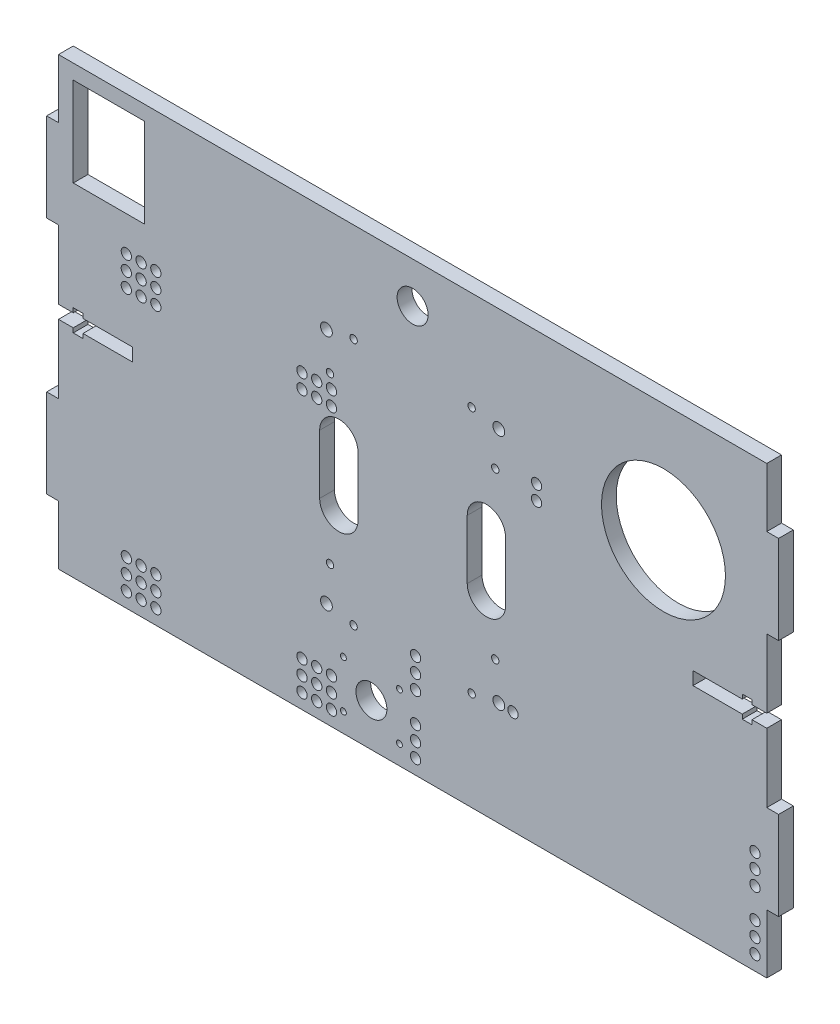
SolidWorks part; units mm, degrees
ref_plane "Front Plane" through (0, 0, 0) normal (0, 0, 1) x (1, 0, 0)
ref_plane "Top Plane" through (0, 0, 0) normal (0, 1, 0) x (1, 0, 0)
ref_plane "Right Plane" through (0, 0, 0) normal (1, 0, 0) x (0, 0, -1)
sketch "Sketch1" plane through (0, 0, 0) normal (0, 0, 1) x (1, 0, 0)
  line L1 (-120, 75.5) -> (120, 75.5)
  line L2 (-120, 75.5) -> (-120, -75.5)
  line L3 (-120, -75.5) -> (120, -75.5)
  line L4 (120, 75.5) -> (120, -75.5)
  dimension "D1" = 240
  dimension "D2" = 120
  dimension "D3" = 151
  dimension "D4" = 75.5
extrude "Boss-Extrude1" add sketch "Sketch1" along normal blind 5
sketch "Sketch2" plane through (0, 0, 0) normal (0, 0, -1) x (-1, 0, 0)
  line L0 (0, 0) -> (54.8158, 0) construction
  circle A0 centre (-20, 42) radius 1.25
  circle A1 centre (28, 28) radius 1.25
  circle A2 centre (20, 42) radius 1.25
  circle A3 centre (-28, 28) radius 1.25
  circle A4 centre (-28, -28) radius 1.25
  circle A5 centre (20, -42) radius 1.25
  circle A6 centre (28, -28) radius 1.25
  circle A7 centre (-20, -42) radius 1.25
extrude "Cut-Extrude1" cut sketch "Sketch2" against normal blind 5
sketch "Sketch5" plane through (0, 0, 0) normal (0, 0, -1) x (-1, 0, 0)
  line L0 (25, -10.5) -> (25, 9.5) construction
  line L1 (18.5, -10.5) -> (18.5, 9.5)
  line L2 (31.5, -10.5) -> (31.5, 9.5)
  line L3 (0, 0) -> (0, -34.3019) construction
  line L4 (-25, -10.5) -> (-25, 9.5) construction
  line L5 (-18.5, -10.5) -> (-18.5, 9.5)
  line L6 (-31.5, -10.5) -> (-31.5, 9.5)
  arc A0 (18.5, -10.5) -> (31.5, -10.5) centre (25, -10.5) ccw
  arc A1 (31.5, 9.5) -> (18.5, 9.5) centre (25, 9.5) ccw
  arc A2 (-18.5, -10.5) -> (-31.5, -10.5) centre (-25, -10.5) cw
  circle A3 centre (28, 28) radius 1.25 construction
  arc A4 (-31.5, 9.5) -> (-18.5, 9.5) centre (-25, 9.5) cw
  point P2 (25, -0.5)
  point P14 (-25, -0.5)
  dimension "D1" = 3
  dimension "D2" = 18.5
  dimension "D3" = 13
  dimension "D4" = 20
extrude "Cut-Extrude2" cut sketch "Sketch5" against normal blind 10
sketch "Sketch7" plane through (0, 0, 0) normal (0, 0, -1) x (-1, 0, 0)
  line L0 (0, 0) -> (0, -54.3684) construction
  line L1 (49.7043, 0) -> (71.9806, 0) construction
  circle A5 centre (29.2076, 40.2173) radius 2
  circle A6 centre (29.2076, -40.2173) radius 2
  circle A7 centre (-29.2076, -40.2173) radius 2
  circle A8 centre (-29.2076, 40.2173) radius 2
  dimension "D9" = 4
  dimension "D10" = 4
extrude "Cut-Extrude4" cut sketch "Sketch7" against normal blind 10
sketch "Sketch8" plane through (0, 0, 0) normal (0, 0, -1) x (-1, 0, 0)
  line L0 (120, 75.5) -> (120, -75.5) construction
  line L2 (120, -75.5) -> (-120, -75.5) construction
  line L8 (95, -75.5) -> (95, -46.5)
  line L9 (73.9, -75.5) -> (95, -75.5)
  line L10 (73.9, -46.5) -> (73.9, -75.5)
  line L11 (95, -46.5) -> (73.9, -46.5)
  dimension "D1" = 25
  dimension "D2" = 21.1
  dimension "D3" = 29
extrude "Cut-Extrude5" [suppressed] cut sketch "Sketch8" against normal blind 10
sketch "Sketch9" plane through (0, 0, 0) normal (0, 0, -1) x (-1, 0, 0)
  line L0 (120, 75.5) -> (120, -75.5) construction
  line L1 (120, 55.5) -> (124, 55.5)
  line L2 (120, 55.5) -> (120, 25.5)
  line L3 (120, 25.5) -> (124, 25.5)
  line L4 (124, 55.5) -> (124, 25.5)
  line L5 (-120, 75.5) -> (120, 75.5) construction
  line L6 (120, -25.5) -> (124, -25.5)
  line L7 (120, -25.5) -> (120, -55.5)
  line L8 (120, -55.5) -> (124, -55.5)
  line L9 (124, -25.5) -> (124, -55.5)
  line L11 (120, -75.5) -> (-120, -75.5) construction
  line L12 (0, 0) -> (0, -172.8228) construction
  line L13 (-124, -25.5) -> (-124, -55.5)
  line L14 (-120, -55.5) -> (-124, -55.5)
  line L15 (-120, -25.5) -> (-120, -55.5)
  line L16 (-120, -25.5) -> (-124, -25.5)
  line L17 (-124, 55.5) -> (-124, 25.5)
  line L18 (-120, 25.5) -> (-124, 25.5)
  line L19 (-120, 55.5) -> (-120, 25.5)
  line L20 (-120, 55.5) -> (-124, 55.5)
  dimension "D1" = 4
  dimension "D2" = 4
  dimension "D3" = 20
  dimension "D4" = 30
  dimension "D5" = 20
  dimension "D6" = 30
extrude "Boss-Extrude2" add sketch "Sketch9" against normal blind 5
sketch "Sketch10" plane through (0, 0, 0) normal (0, 0, -1) x (-1, 0, 0)
  line L0 (-120, 0) -> (-90.1273, 0) construction
  line L1 (-120, -25.5) -> (-120, 25.5) construction
  line L2 (-120, 2.2) -> (-115, 2.2)
  line L3 (-115, 2.2) -> (-115, 3.7)
  line L4 (-115, 3.7) -> (-111.7, 3.7)
  line L5 (-111.7, 3.7) -> (-111.7, 2.2)
  line L6 (-111.7, 2.2) -> (-95, 2.2)
  line L7 (-95, 2.2) -> (-95, -2.2)
  line L8 (-95, -2.2) -> (-111.7, -2.2)
  line L9 (-111.7, -2.2) -> (-111.7, -3.7)
  line L10 (-111.7, -3.7) -> (-115, -3.7)
  line L11 (-115, -3.7) -> (-115, -2.2)
  line L12 (-115, -2.2) -> (-120, -2.2)
  line L13 (0, 0) -> (0, -23.4808) construction
  line L14 (120, 0) -> (90.1273, 0) construction
  line L15 (115, -2.2) -> (120, -2.2)
  line L16 (115, -3.7) -> (115, -2.2)
  line L17 (111.7, -3.7) -> (115, -3.7)
  line L18 (111.7, -2.2) -> (111.7, -3.7)
  line L19 (95, -2.2) -> (111.7, -2.2)
  line L20 (95, 2.2) -> (95, -2.2)
  line L21 (111.7, 2.2) -> (95, 2.2)
  line L22 (111.7, 3.7) -> (111.7, 2.2)
  line L23 (115, 3.7) -> (111.7, 3.7)
  line L24 (115, 2.2) -> (115, 3.7)
  line L25 (120, 2.2) -> (115, 2.2)
  line L26 (-120, -2.2) -> (-120, 2.2)
  line L27 (120, 2.2) -> (120, -2.2)
  dimension "D1" = 4.4
  dimension "D2" = 1.5
  dimension "D3" = 3.3
  dimension "D4" = 5
  dimension "D5" = 25
extrude "Cut-Extrude6" cut sketch "Sketch10" against normal blind 5
sketch "Sketch13" plane through (0, 0, 0) normal (0, 0, -1) x (-1, 0, 0)
  circle A1 centre (-85, 35.5) radius 21
  point P1 (0, 0)
  dimension "D1" = 42
extrude "Cut-Extrude9" cut sketch "Sketch13" against normal blind 10
sketch "Sketch15" plane through (0, 0, 0) normal (0, 0, -1) x (-1, 0, 0)
  line L0 (120, -75.5) -> (-120, -75.5) construction
  line L1 (-124, -25.5) -> (-124, -55.5) construction
  circle A0 centre (-34, -40.5) radius 1.75
  dimension "D3" = 3.5
  dimension "D1" = 35
  dimension "D2" = 90
extrude "Cut-Extrude11" cut sketch "Sketch15" against normal blind 10
sketch "Sketch16" plane through (0, 0, 0) normal (0, 0, -1) x (-1, 0, 0)
  line L0 (120, -75.5) -> (-120, -75.5) construction
  line L1 (-124, 55.5) -> (-124, 25.5) construction
  line L2 (120, -75.5) -> (-120, -75.5) construction
  line L4 (124, -55.5) -> (124, -25.5) construction
  circle A0 centre (-42, 25.5) radius 1.75
  circle A1 centre (87, -70.5) radius 1.75
  circle A3 centre (27.5, -70.5) radius 1.75
  circle A4 centre (87, 18.5) radius 1.75
  circle A5 centre (27.5, 18.5) radius 1.75
  circle A6 centre (-42, 30.5) radius 1.75
  circle A7 centre (27.5, 23.5) radius 1.75
  circle A8 centre (87, -65.5) radius 1.75
  circle A9 centre (87, 23.5) radius 1.75
  circle A10 centre (27.5, -65.5) radius 1.75
  circle A13 centre (87, -60.5) radius 1.75
  circle A14 centre (87, 28.5) radius 1.75
  circle A15 centre (27.5, -60.5) radius 1.75
  circle A16 centre (27.5, 28.5) radius 1.75 [skipped]
  circle A17 centre (-42, 35.5) radius 1.75 [skipped]
  circle A18 centre (32.5, -70.5) radius 1.75
  circle A19 centre (92, -70.5) radius 1.75
  circle A20 centre (32.5, -65.5) radius 1.75
  circle A21 centre (32.5, -60.5) radius 1.75
  circle A22 centre (92, -65.5) radius 1.75
  circle A23 centre (92, -60.5) radius 1.75
  circle A24 centre (32.5, 18.5) radius 1.75
  circle A25 centre (32.5, 23.5) radius 1.75
  circle A26 centre (92, 23.5) radius 1.75
  circle A27 centre (92, 18.5) radius 1.75
  circle A28 centre (92, 28.5) radius 1.75
  circle A29 centre (37.5, -70.5) radius 1.75
  circle A30 centre (97, -70.5) radius 1.75
  circle A31 centre (37.5, -65.5) radius 1.75
  circle A32 centre (37.5, -60.5) radius 1.75
  circle A33 centre (97, -65.5) radius 1.75
  circle A34 centre (97, -60.5) radius 1.75
  circle A35 centre (37.5, 18.5) radius 1.75
  circle A36 centre (37.5, 23.5) radius 1.75
  circle A37 centre (97, 23.5) radius 1.75
  circle A38 centre (97, 18.5) radius 1.75
  circle A39 centre (97, 28.5) radius 1.75
  dimension "D3" = 3.5
  dimension "D4" = 5
  dimension "D6" = 3.5
  dimension "D7" = 59.5
  dimension "D8" = 3.5
  dimension "D9" = 3.5
  dimension "D10" = 89
  dimension "D11" = 3.5
  dimension "D1" = 101
  dimension "D2" = 82
  dimension "D5" = 37
  dimension "D12" = 3
  dimension "D13" = 3
extrude "Cut-Extrude12" cut sketch "Sketch16" against normal blind 10
sketch "Sketch17" plane through (0, 0, 0) normal (0, 0, -1) x (-1, 0, 0)
  line L0 (-120, -75.5) -> (-120, -55.5) construction
  line L1 (120, -75.5) -> (-120, -75.5) construction
  circle A0 centre (-116, -70.5) radius 1.75
  circle A1 centre (-116, -50.5) radius 1.75
  circle A2 centre (-1, -50.5) radius 1.75
  circle A3 centre (-1, -70.5) radius 1.75
  circle A4 centre (-116, -45.5) radius 1.75
  circle A5 centre (-116, -65.5) radius 1.75
  circle A6 centre (-1, -45.5) radius 1.75
  circle A7 centre (-1, -65.5) radius 1.75
  circle A8 centre (-116, -40.5) radius 1.75
  circle A9 centre (-116, -60.5) radius 1.75
  circle A10 centre (-1, -40.5) radius 1.75
  circle A11 centre (-1, -60.5) radius 1.75
  dimension "D2" = 3.5
  dimension "D3" = 5
  dimension "D4" = 3.5
  dimension "D5" = 20
  dimension "D6" = 3.5
  dimension "D7" = 3.5
  dimension "D8" = 115
  dimension "D1" = 4
  dimension "D9" = 3
extrude "Cut-Extrude13" cut sketch "Sketch17" against normal blind 10
sketch "Sketch20" plane through (0, 0, 0) normal (0, 0, -1) x (-1, 0, 0)
  line L0 (120, 75.5) -> (120, 55.5) construction
  line L1 (-120, 75.5) -> (120, 75.5) construction
  line L8 (90.8, 70.5) -> (90.8, 40.3)
  line L9 (115, 70.5) -> (90.8, 70.5)
  line L10 (115, 40.3) -> (115, 70.5)
  line L11 (90.8, 40.3) -> (115, 40.3)
  dimension "D1" = 5
  dimension "D2" = 5
  dimension "D3" = 24.2
  dimension "D4" = 30.2
extrude "Cut-Extrude14" cut sketch "Sketch20" against normal blind 10
sketch "Sketch21" plane through (0, 0, 0) normal (0, 0, -1) x (-1, 0, 0)
  circle A2 centre (13.9635, -61) radius 5.25
  dimension "D1" = 10.5
extrude "Cut-Extrude15" cut sketch "Sketch21" against normal blind 5
sketch "Sketch22" plane through (0, 0, 0) normal (0, 0, -1) x (-1, 0, 0)
  circle A4 centre (23.4635, -53) radius 1
  circle A5 centre (23.4635, -69) radius 1
  circle A6 centre (4.4635, -53) radius 1
  circle A7 centre (4.4635, -69) radius 1
extrude "Cut-Extrude16" cut sketch "Sketch22" against normal blind 5
sketch "Sketch23" plane through (0, 0, 0) normal (0, 0, -1) x (-1, 0, 0)
  circle A0 centre (0, 61.6538) radius 5.25
  dimension "D1" = 10.5
extrude "Cut-Extrude17" cut sketch "Sketch23" against normal blind 10
sketch "Sketch26" plane through (0, 0, 0) normal (0, 0, -1) x (-1, 0, 0)
  line L1 (-56.5, 75.5) -> (-81.5, 75.5)
  line L2 (-56.5, 75.5) -> (-56.5, 70.5)
  line L3 (-56.5, 70.5) -> (-81.5, 70.5)
  line L4 (-81.5, 75.5) -> (-81.5, 70.5)
extrude "Cut-Extrude20" [suppressed] cut sketch "Sketch26" against normal blind 10
sketch "Sketch27" [suppressed] plane through (0, 0, 0) normal (0, 0, -1) x (-1, 0, 0)
  line L0 (-69, 70.5) -> (-69, 54.5) construction
  line L1 (-81.5, 70.5) -> (-56.5, 70.5) construction
  line L2 (-71, 70.5) -> (-71, 65.5)
  line L3 (-71, 65.5) -> (-72.5, 65.5)
  line L4 (-72.5, 65.5) -> (-72.5, 62.3)
  line L5 (-72.5, 62.3) -> (-71, 62.3)
  line L6 (-71, 62.3) -> (-71, 54.5)
  line L7 (-71, 54.5) -> (-67, 54.5)
  line L8 (-67, 54.5) -> (-67, 62.3)
  line L9 (-67, 62.3) -> (-65.5, 62.3)
  line L10 (-65.5, 62.3) -> (-65.5, 65.5)
  line L11 (-65.5, 65.5) -> (-67, 65.5)
  line L12 (-67, 65.5) -> (-67, 70.5)
  line L13 (-67, 70.5) -> (-71, 70.5)
  dimension "D1" = 2
  dimension "D2" = 2
  dimension "D3" = 1.5
  dimension "D4" = 1.5
  dimension "D5" = 3.2
  dimension "D6" = 3.2
  dimension "D7" = 5
  dimension "D8" = 16
extrude "Cut-Extrude21" [suppressed] cut sketch "Sketch27" against normal blind 5
